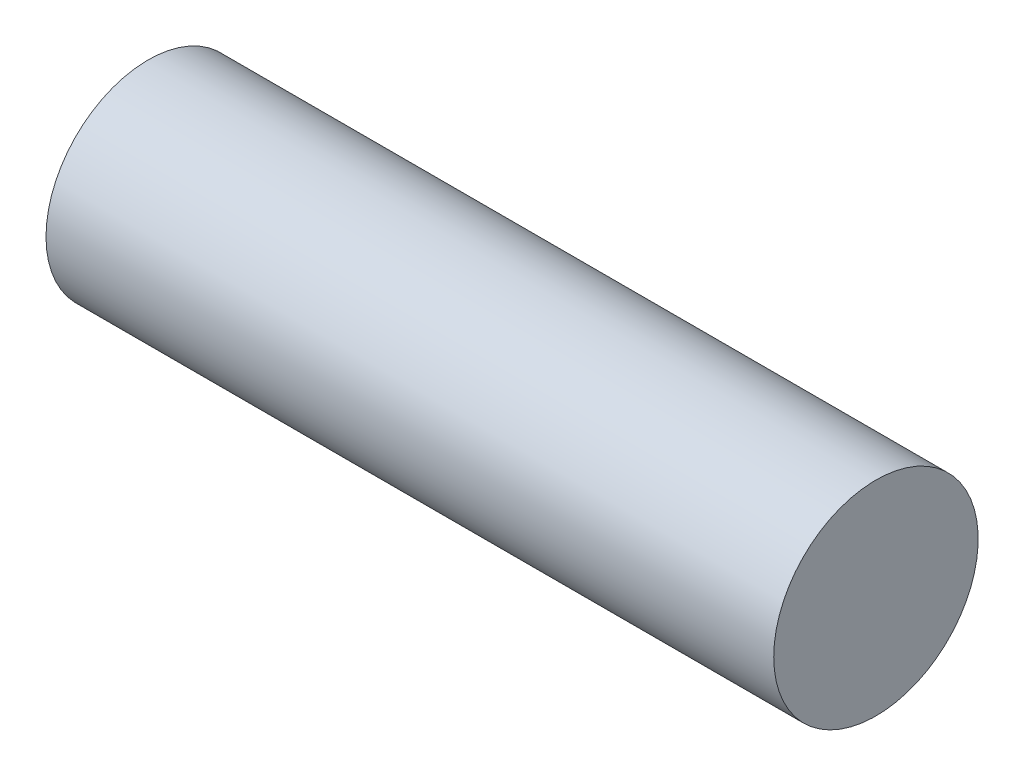
SolidWorks part; units mm, degrees
ref_plane "Plan de face" through (0, 0, 0) normal (0, 0, 1) x (1, 0, 0)
ref_plane "Plan de dessus" through (0, 0, 0) normal (0, 1, 0) x (1, 0, 0)
ref_plane "Plan de droite" through (0, 0, 0) normal (1, 0, 0) x (0, 0, -1)
sketch "Esquisse1" plane through (0, 26.1983, -67.0969) normal (0, 1, 0) x (1, 0, 0)
  line L1 (-34.1918, 39.0314) -> (-349.381, 39.0314)
  line L2 (-349.381, 39.0314) -> (-349.381, -5.2397)
  line L4 (-349.381, -5.2397) -> (-34.1918, -5.2397)
  line L6 (-34.1918, -5.2397) -> (-34.1918, 39.0314)
revolve "Révolution1" add sketch "Esquisse1" angle 360 about L4
